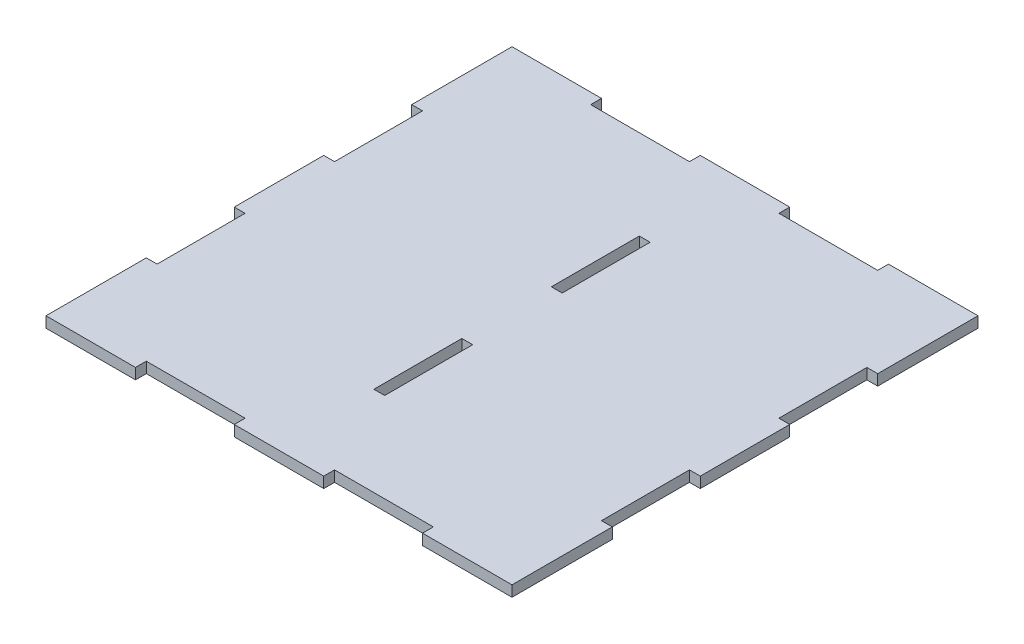
SolidWorks part; units mm, degrees
material "Бальса"
ref_plane "Спереди" through (0, 0, 0) normal (0, 0, 1) x (1, 0, 0)
ref_plane "Сверху" through (0, 0, 0) normal (0, 1, 0) x (1, 0, 0)
ref_plane "Справа" through (0, 0, 0) normal (1, 0, 0) x (0, 0, -1)
sketch "Эскиз1" plane through (0, 0, 0) normal (0, 1, 0) x (1, 0, 0)
  line L1 (0, 0) -> (250, 0)
  line L2 (0, 0) -> (0, 250)
  line L3 (0, 250) -> (250, 250)
  line L4 (250, 0) -> (250, 250)
  dimension "D1" = 250
  dimension "D2" = 250
extrude "Бобышка-Вытянуть1" add sketch "Эскиз1" along normal blind 5.8
sketch "Эскиз2" plane through (0, 0, 0) normal (0, -1, 0) x (1, 0, 0)
  line L1 (48, -5.8) -> (101, -5.8)
  line L2 (48, -5.8) -> (48, 0)
  line L3 (48, 0) -> (101, 0)
  line L4 (101, -5.8) -> (101, 0)
  line L5 (0, -250) -> (0, 0) construction
  line L6 (149, -5.8) -> (202, -5.8)
  line L7 (149, -5.8) -> (149, 0)
  line L8 (149, 0) -> (202, 0)
  line L9 (202, -5.8) -> (202, 0)
  line L10 (122.1, -53.8) -> (127.9, -53.8)
  line L11 (122.1, -53.8) -> (122.1, -101)
  line L12 (122.1, -101) -> (127.9, -101)
  line L13 (127.9, -53.8) -> (127.9, -101)
  line L14 (5.8, -101) -> (0, -101)
  line L15 (5.8, -101) -> (5.8, -53.8)
  line L16 (5.8, -53.8) -> (0, -53.8)
  line L17 (0, -101) -> (0, -53.8)
  line L20 (5.8, -149) -> (0, -149)
  line L21 (5.8, -149) -> (5.8, -196.2)
  line L22 (5.8, -196.2) -> (0, -196.2)
  line L23 (0, -149) -> (0, -196.2)
  line L25 (122.1, -149) -> (127.9, -149)
  line L26 (122.1, -149) -> (122.1, -196.2)
  line L27 (122.1, -196.2) -> (127.9, -196.2)
  line L28 (127.9, -149) -> (127.9, -196.2)
  line L29 (48, -244.2) -> (101, -244.2)
  line L30 (48, -244.2) -> (48, -250)
  line L31 (48, -250) -> (101, -250)
  line L32 (101, -244.2) -> (101, -250)
  line L35 (149, -244.2) -> (202, -244.2)
  line L36 (149, -244.2) -> (149, -250)
  line L37 (149, -250) -> (202, -250)
  line L38 (202, -244.2) -> (202, -250)
  line L39 (250, 0) -> (250, -250) construction
  line L40 (244.2, -196.2) -> (250, -196.2)
  line L41 (244.2, -196.2) -> (244.2, -149)
  line L42 (244.2, -149) -> (250, -149)
  line L43 (250, -196.2) -> (250, -149)
  line L45 (0, 0) -> (250, 0) construction
  line L46 (244.2, -101) -> (250, -101)
  line L47 (244.2, -101) -> (244.2, -53.8)
  line L48 (244.2, -53.8) -> (250, -53.8)
  line L49 (250, -101) -> (250, -53.8)
  line L50 (250, -250) -> (0, -250) construction
  line L51 (5.8, -149) -> (122.1, -149) construction
  line L52 (127.9, -149) -> (244.2, -149) construction
  line L53 (127.9, -101) -> (244.2, -101) construction
  line L54 (127.9, -53.8) -> (244.2, -53.8) construction
  line L55 (127.9, -196.2) -> (244.2, -196.2) construction
  line L56 (125, 0) -> (125, -53.8) construction
  line L57 (125, -101) -> (125, -149) construction
  line L58 (122.1, -149) -> (122.1, -101) construction
  dimension "D1" = 48
  dimension "D2" = 48
  dimension "D3" = 48
  dimension "D4" = 48
  dimension "D5" = 48
  dimension "D6" = 48
  dimension "D7" = 48
  dimension "D8" = 5.8
  dimension "D9" = 48
  dimension "D10" = 48
  dimension "D11" = 5.8
  dimension "D12" = 48
  dimension "D13" = 48
  dimension "D14" = 48
  dimension "D15" = 5.8
  dimension "D16" = 5.8
  dimension "D17" = 5.8
extrude "Вырез-Вытянуть1" cut sketch "Эскиз2" against normal up to next
